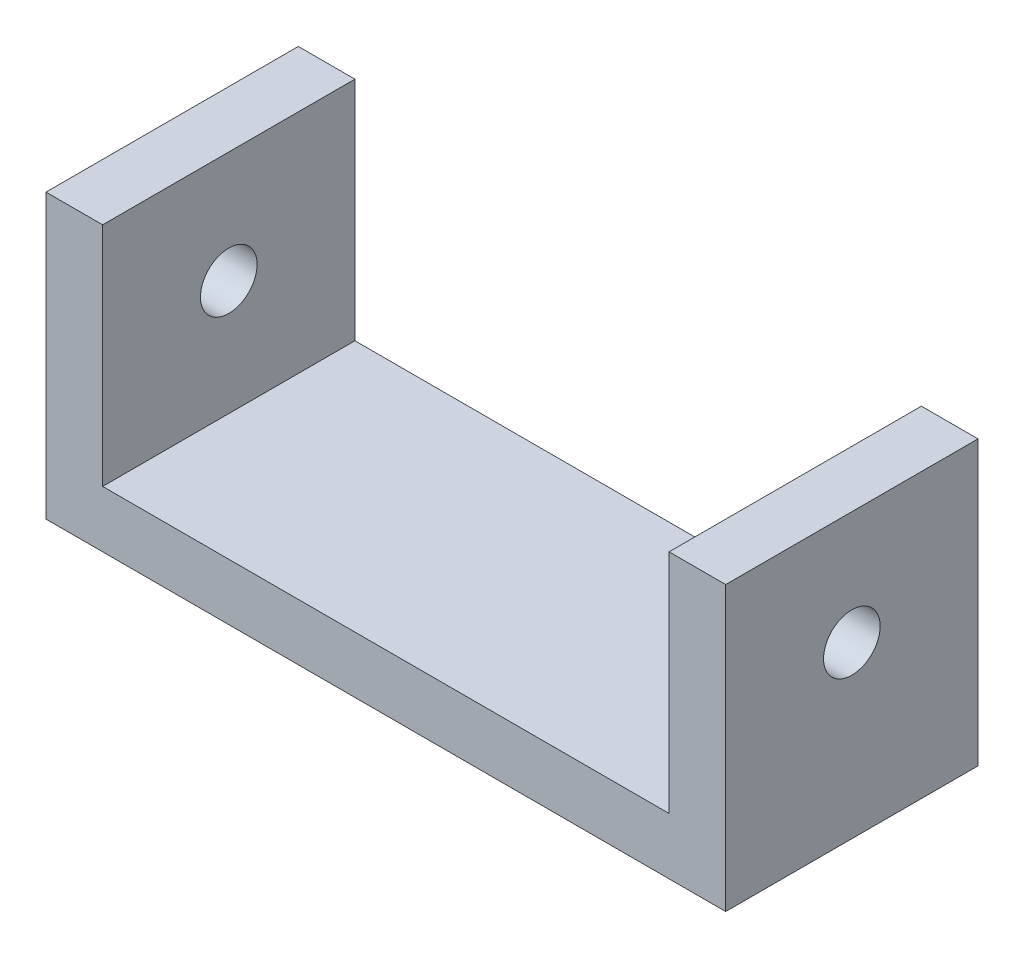
SolidWorks part; units mm, degrees
ref_plane "Front Plane" through (0, 0, 0) normal (0, 0, 1) x (1, 0, 0)
ref_plane "Top Plane" through (0, 0, 0) normal (0, 1, 0) x (1, 0, 0)
ref_plane "Right Plane" through (0, 0, 0) normal (1, 0, 0) x (0, 0, -1)
sketch "Sketch1" plane through (0, 0, 0) normal (0, 1, 0) x (1, 0, 0)
  line L1 (-38.1, 14.1421) -> (38.1, 14.1421)
  line L2 (-38.1, 14.1421) -> (-38.1, -14.1421)
  line L3 (-38.1, -14.1421) -> (38.1, -14.1421)
  line L4 (38.1, 14.1421) -> (38.1, -14.1421)
  line L5 (-38.1, 14.1421) -> (38.1, -14.1421) construction
  line L6 (-38.1, -14.1421) -> (38.1, 14.1421) construction
  point P0 (0, 0)
  dimension "D1" = 76.2
extrude "Boss-Extrude1" add sketch "Sketch1" along normal blind 6.35
sketch "Sketch2" plane through (0, 6.35, 0) normal (0, 1, 0) x (1, 0, 0)
  line L0 (-38.1, -14.1421) -> (38.1, -14.1421) construction
  line L1 (-38.1, 14.1421) -> (-31.75, 14.1421)
  line L2 (-38.1, 14.1421) -> (-38.1, -14.1421)
  line L3 (-38.1, -14.1421) -> (-31.75, -14.1421)
  line L4 (-31.75, 14.1421) -> (-31.75, -14.1421)
  line L6 (38.1, 14.1421) -> (31.75, 14.1421)
  line L7 (38.1, 14.1421) -> (38.1, -14.1421)
  line L8 (38.1, -14.1421) -> (31.75, -14.1421)
  line L9 (31.75, 14.1421) -> (31.75, -14.1421)
  dimension "D1" = 6.35
  dimension "D2" = 6.35
extrude "Boss-Extrude2" add sketch "Sketch2" along normal blind 25.4
sketch "Sketch3" plane through (-38.1, 0, 0) normal (-1, 0, 0) x (0, 0, 1)
  line L0 (-14.1421, 6.7458) -> (14.1421, 31.75) construction
  line L1 (-14.1421, 31.75) -> (-14.1421, 0) construction
  line L2 (-14.1421, 31.75) -> (14.1421, 6.7458) construction
  line L3 (14.1421, 31.75) -> (14.1421, 0) construction
  circle A0 centre (0, 19.2479) radius 3.175
  dimension "D1" = 6.35
extrude "Cut-Extrude1" cut sketch "Sketch3" against normal blind 6.35
sketch "Sketch4" plane through (38.1, 0, 0) normal (1, 0, 0) x (0, 0, -1)
  line L0 (-14.1421, 6.35) -> (14.1421, 31.75) construction
  line L1 (-14.1421, 31.75) -> (14.1421, 6.35) construction
  circle A0 centre (0, 19.05) radius 3.175
  dimension "D1" = 6.35
extrude "Cut-Extrude2" cut sketch "Sketch4" against normal blind 7.62 contours A0
